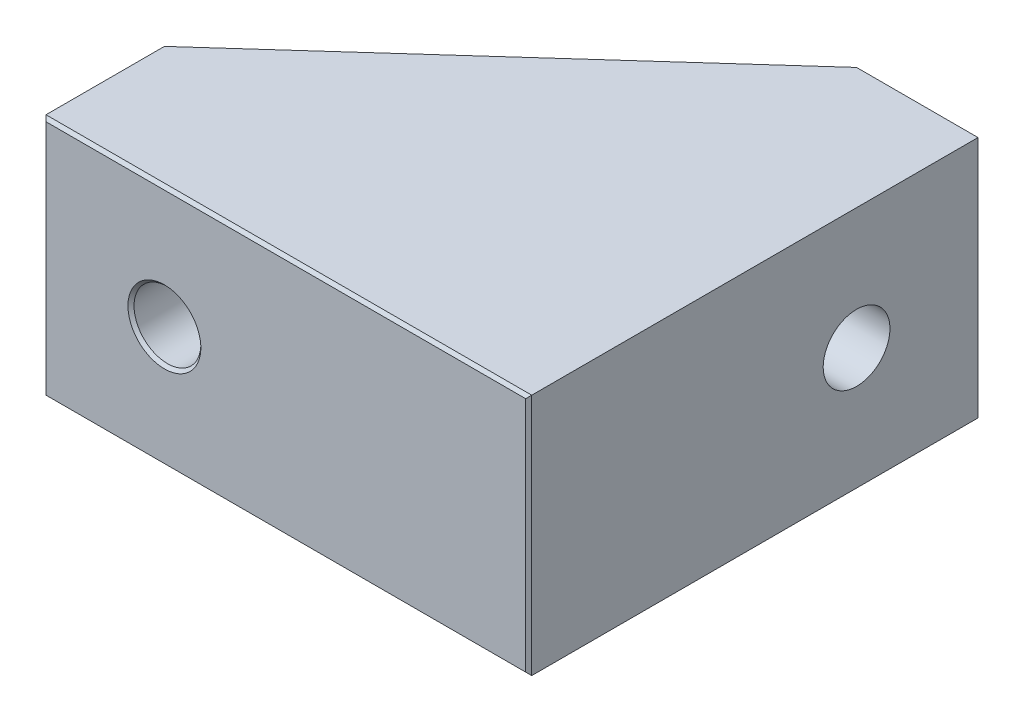
SolidWorks part; units mm, degrees
ref_plane "Front Plane" through (0, 0, 0) normal (0, 0, 1) x (1, 0, 0)
ref_plane "Top Plane" through (0, 0, 0) normal (0, 1, 0) x (1, 0, 0)
ref_plane "Right Plane" through (0, 0, 0) normal (1, 0, 0) x (0, 0, -1)
sketch "Sketch1" plane through (0, 0, 0) normal (0, 1, 0) x (1, 0, 0)
  line L0 (0, 47.1541) -> (0, -43.1203) construction
  line L1 (-67.0451, 0) -> (61.8985, 0) construction
  line L2 (0, 37) -> (-10, 37)
  line L3 (-10, 37) -> (-10, 10)
  line L4 (-10, 10) -> (-40, 10)
  line L5 (-40, 10) -> (-40, 0)
  line L6 (-40, 0) -> (0, 0)
  line L7 (0, 0) -> (0, 37)
  point P10 (-67.0451, 0)
  dimension "D1" = 37
  dimension "D2" = 10
  dimension "D3" = 10
  dimension "D4" = 40
extrude "Boss-Extrude1" add sketch "Sketch1" along normal blind 20
sketch "Sketch2" plane through (-10, 0, 0) normal (-1, 0, 0) x (0, 0, 1)
  line L0 (-37, 21.8968) -> (-37, -6.456) construction
  circle A0 centre (-27, 10) radius 2.75
  dimension "D1" = 5.5
  dimension "D2" = 10
  dimension "D3" = 10
extrude "Cut-Extrude1" cut sketch "Sketch2" against normal blind 20
sketch "Sketch3" plane through (0, 0, -10) normal (0, 0, -1) x (-1, 0, 0)
  line L0 (40, 21.9312) -> (40, -2.6492) construction
  circle A0 centre (30, 10) radius 2.75
  dimension "D1" = 5.5
  dimension "D2" = 10
  dimension "D3" = 10
extrude "Cut-Extrude2" cut sketch "Sketch3" against normal blind 20
sketch "Sketch4" plane through (0, 0, 0) normal (0, -1, 0) x (1, 0, 0)
  line L0 (-40, -10) -> (-10, -10)
  line L1 (-10, -10) -> (-10, -37)
  line L2 (-10, -37) -> (-40, -10)
extrude "Boss-Extrude2" add sketch "Sketch4" against normal blind 4.5
sketch "Sketch5" plane through (0, 20, 0) normal (0, 1, 0) x (1, 0, 0)
  line L0 (-40, 10) -> (-10, 10)
  line L1 (-10, 10) -> (-10, 37)
  line L2 (-10, 37) -> (-40, 10)
extrude "Boss-Extrude3" add sketch "Sketch5" against normal blind 4.5
chamfer "Chamfer1" distance 0.25 angle 45 7 edges at (-40, 10, 0) (-20, 20, 0) (0, 10, 0) (-20, 0, 0) (-32.75, 10, 0) (-10, 10, -24.25) (-32.75, 10, -10)
